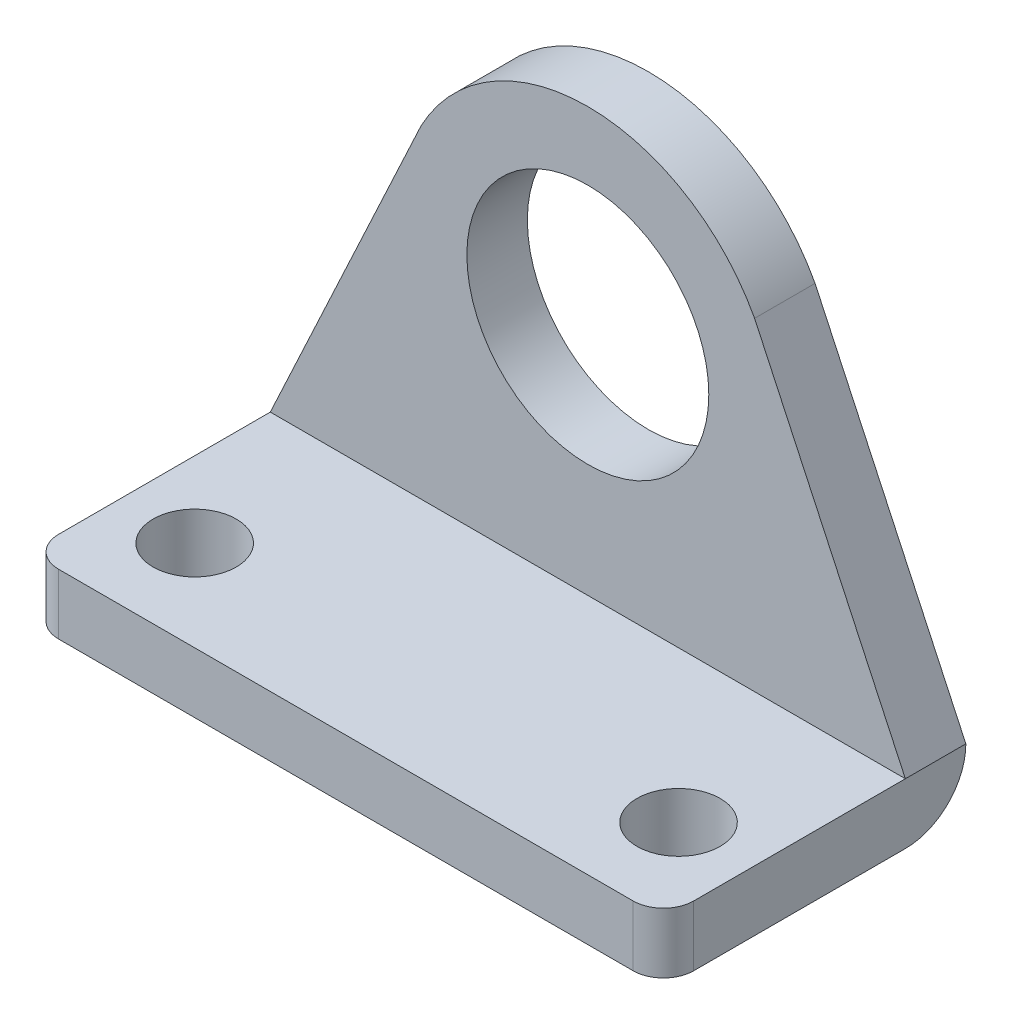
SolidWorks part; units mm, degrees
ref_plane "Front Plane" through (0, 0, 0) normal (0, 0, 1) x (1, 0, 0)
ref_plane "Top Plane" through (0, 0, 0) normal (0, 1, 0) x (1, 0, 0)
ref_plane "Right Plane" through (0, 0, 0) normal (1, 0, 0) x (0, 0, -1)
sketch "Sketch1" plane through (0, 0, 0) normal (0, 0, 1) x (1, 0, 0)
  line L0 (0, 0) -> (9.9719, 21.3848)
  line L1 (0, 0) -> (42, 0)
  line L2 (32.0281, 21.3848) -> (42, 0)
  arc A1 (9.9719, 21.3848) -> (32.0281, 21.3848) centre (21, 15.5) cw
  circle A2 centre (21, 15.5) radius 8
  point P7 (21, 28)
  dimension "D1" = 28
  dimension "D2" = 115
  dimension "D5" = 12.5
  dimension "D6" = 16
  dimension "D3" = 42
  dimension "D4" = 115
extrude "Boss-Extrude1" add sketch "Sketch1" along normal blind 4
sketch "Sketch2" plane through (0, 0, 0) normal (0, -1, 0) x (-1, 0, 0)
  line L0 (0, -4) -> (0, -18)
  line L1 (-2, -20) -> (-40, -20)
  line L2 (-42, -18) -> (-42, -4)
  line L3 (-42, -4) -> (0, -4)
  line L4 (0, 0) -> (-42, 0) construction
  circle A0 centre (-37, -14) radius 2.75
  circle A1 centre (-5, -14) radius 2.75
  arc A2 (-2, -20) -> (0, -18) centre (-2, -18) ccw
  arc A3 (-40, -20) -> (-42, -18) centre (-40, -18) cw
  point P13 (0, 0)
  dimension "D2" = 14
  dimension "D3" = 5.5
  dimension "D4" = 32
  dimension "D5" = 5
  dimension "D6" = 2
  dimension "D1" = 20
extrude "Boss-Extrude2" add sketch "Sketch2" along normal blind 4 separate body
sketch "Sketch3" plane through (0, 0, 0) normal (-1, 0, 0) x (0, 0, 1)
  line L0 (4, 0) -> (0, 0) construction
  line L1 (4, -4) -> (4, 0) construction
  line L2 (4, 0) -> (0, 0)
  line L3 (4, -4) -> (4, 0)
  arc A0 (0, 0) -> (4, -4) centre (4, 0) ccw
extrude "Boss-Extrude3" add sketch "Sketch3" against normal up to surface (42 mm away) up to face at (42, -2, 11)
